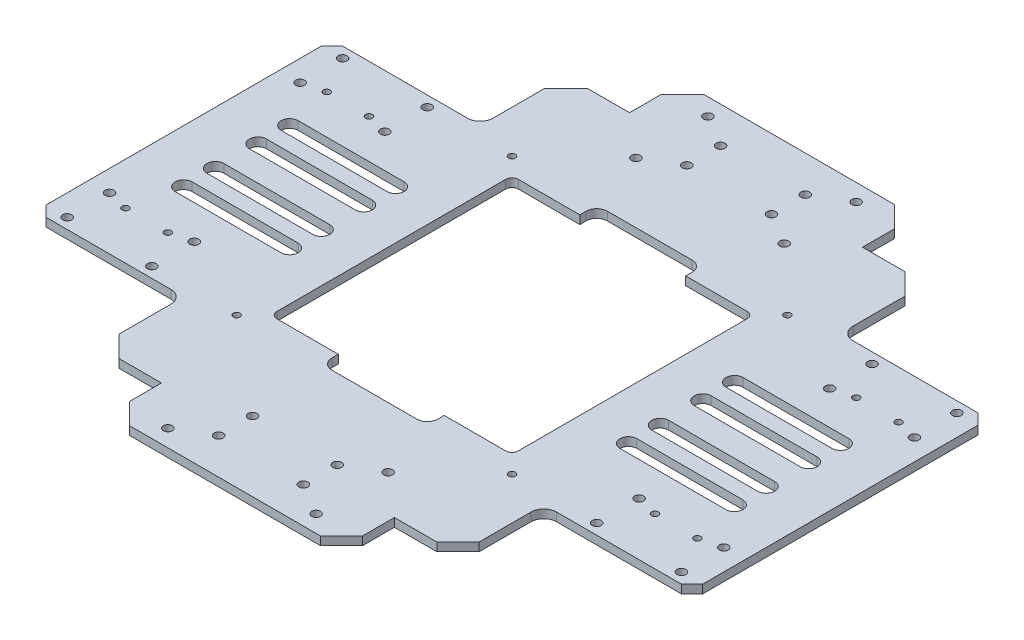
SolidWorks part; units mm, degrees
ref_plane "前视基准面" through (0, 0, 0) normal (0, 0, 1) x (1, 0, 0)
ref_plane "上视基准面" through (0, 0, 0) normal (0, 1, 0) x (1, 0, 0)
ref_plane "右视基准面" through (0, 0, 0) normal (1, 0, 0) x (0, 0, -1)
sketch "草图1" plane through (0, 0, 0) normal (0, 1, 0) x (1, 0, 0)
  line L0 (-55, 135.4999) -> (-55, -135.4999)
  line L1 (-55, -135.4999) -> (55, -135.4999)
  line L2 (55, -135.4999) -> (55, 135.4999)
  line L3 (55, 135.4999) -> (-55, 135.4999)
  circle A0 centre (-35, 127.4999) radius 2.1
  circle A1 centre (-20, 118.4999) radius 2.1
  circle A2 centre (20, 118.4999) radius 2.1
  circle A3 centre (35, 127.4999) radius 2.1
  circle A4 centre (20, 102.4999) radius 2.1
  circle A5 centre (35, 93.4999) radius 2.1
  circle A6 centre (-35, 93.4999) radius 2.1
  circle A7 centre (-20, 102.4999) radius 2.1
  circle A8 centre (-35, -127.4999) radius 2.1
  circle A9 centre (-20, -118.4999) radius 2.1
  circle A10 centre (-20, -102.4999) radius 2.1
  circle A11 centre (20, -118.4999) radius 2.1
  circle A12 centre (20, -102.4999) radius 2.1
  circle A13 centre (35, -93.4999) radius 2.1
  circle A14 centre (35, -127.4999) radius 2.1
extrude "凸台-拉伸1" add sketch "草图1" along normal blind 4
chamfer "倒角1" distance 10 angle 45 4 edges at (-55, 2, 135.4999) (55, 2, 135.4999) (55, 2, -135.4999) (-55, 2, -135.4999)
sketch "草图2" plane through (0, 4, 0) normal (0, 1, 0) x (1, 0, 0)
  line L0 (-25, 45) -> (-40, 30)
  line L1 (-25, -65) -> (25, -65)
  line L2 (-25, -65) -> (-25, -45)
  line L3 (-25, 65) -> (25, 65)
  line L4 (25, -65) -> (25, -45)
  line L5 (-25, -65) -> (25, 65) construction
  line L6 (-25, 65) -> (25, -65) construction
  line L7 (-40, 30) -> (-40, -30)
  line L8 (25, 45) -> (25, 65)
  line L9 (-25, 45) -> (-25, 65)
  line L10 (0, 65) -> (0, -65) construction
  line L11 (25, 0) -> (-25, 0) construction
  line L13 (25, 45) -> (40, 30)
  line L14 (40, 30) -> (40, -30)
  line L15 (25, -45) -> (40, -30)
  line L16 (-25, -45) -> (-40, -30)
  point P0 (0, 0)
  dimension "D1" = 130
  dimension "D2" = 50
  dimension "D5" = 20
extrude "切除-拉伸1" cut sketch "草图2" against normal blind 4
fillet "圆角1" radius 5 4 edges at (-25, 2, 65) (25, 2, 65) (25, 2, -65) (-25, 2, -65)
sketch "草图3" plane through (0, 4, 0) normal (0, 1, 0) x (1, 0, 0)
  line L0 (55, 110.4999) -> (85, 110.4999)
  line L1 (-55, 125.4999) -> (-55, -125.4999) construction
  line L2 (-85, 93.4999) -> (-85, -102.4999)
  line L3 (55, -102.4999) -> (55, 93.4999)
  line L4 (-55, -102.4999) -> (-55, 93.4999)
  line L5 (0, 135.4999) -> (0, -135.4999) construction
  line L6 (45, 135.4999) -> (-45, 135.4999) construction
  line L7 (-45, -135.4999) -> (45, -135.4999) construction
  line L10 (85, 93.4999) -> (85, -102.4999)
  line L12 (55, -125.4999) -> (55, 125.4999) construction
  line L13 (-55, 110.4999) -> (-85, 110.4999)
  line L14 (-85, 110.4999) -> (-85, 93.4999)
  line L15 (-55, 93.4999) -> (-55, 110.4999)
  line L16 (85, 110.4999) -> (85, 93.4999)
  line L17 (55, 110.4999) -> (55, 93.4999)
  line L20 (-55, -110.4999) -> (-85, -110.4999)
  line L21 (-85, -110.4999) -> (-85, -102.4999)
  line L22 (-55, -102.4999) -> (-55, -110.4999)
  line L23 (85, -102.4999) -> (85, -110.4999)
  line L24 (85, -110.4999) -> (55, -110.4999)
  line L25 (55, -110.4999) -> (55, -102.4999)
extrude "凸台-拉伸2" add sketch "草图3" against normal blind 4
chamfer "倒角2" distance 10 angle 45 4 edges at (-85, 2, 110.4999) (85, 2, 110.4999) (85, 2, -110.4999) (-85, 2, -110.4999)
fillet "圆角3" radius 5 4 edges at (-40, 2, 30) (40, 2, 30) (40, 2, -30) (-40, 2, -30)
sketch "草图5" plane through (0, 4, 0) normal (0, 1, 0) x (1, 0, 0)
  line L1 (-65, -65) -> (65, -65) construction
  line L2 (-65, -65) -> (-65, 65) construction
  line L3 (-65, 65) -> (65, 65) construction
  line L4 (65, -65) -> (65, 65) construction
  line L5 (-65, -65) -> (65, 65) construction
  line L6 (-65, 65) -> (65, -65) construction
  circle A0 centre (-65, 65) radius 1.6
  circle A1 centre (65, 65) radius 1.6
  circle A2 centre (65, -65) radius 1.6
  circle A3 centre (-65, -65) radius 1.6
  point P0 (0, 0)
  dimension "D1" = 130
  dimension "D2" = 130
extrude "切除-拉伸2" cut sketch "草图5" against normal blind 4
sketch "草图7" plane through (0, 4, 0) normal (0, 1, 0) x (1, 0, 0)
  line L0 (-85, 0) -> (-85, 70)
  line L1 (-85, 100.4999) -> (-85, -100.4999) construction
  line L2 (-85, 70) -> (-155, 70)
  line L3 (-155, 70) -> (-155, -70)
  line L4 (-155, -70) -> (-85, -70)
  line L5 (-85, -70) -> (-85, 0)
  line L6 (85, 70) -> (155, 70)
  line L7 (85, -100.4999) -> (85, 100.4999) construction
  line L8 (155, 70) -> (155, -70)
  line L9 (155, -70) -> (85, -70)
  line L10 (85, -70) -> (85, 70)
extrude "凸台-拉伸3" add sketch "草图7" against normal blind 4
fillet "圆角4" radius 6 12 edges
sketch "草图8" plane through (0, 4, 0) normal (0, 1, 0) x (1, 0, 0)
  line L0 (0, 135.4999) -> (0, 0) construction
  circle A0 centre (105, 65) radius 2.1
  circle A1 centre (145, 65) radius 2.1
  circle A2 centre (145, 45) radius 2.1
  circle A3 centre (105, 45) radius 2.1
  circle A4 centre (145, -45) radius 2.1
  circle A5 centre (145, -65) radius 2.1
  circle A6 centre (105, -65) radius 2.1
  circle A7 centre (105, -45) radius 2.1
  circle A8 centre (-145, 65) radius 2.1
  circle A9 centre (-105, 65) radius 2.1
  circle A10 centre (-105, 45) radius 2.1
  circle A11 centre (-145, 45) radius 2.1
  circle A12 centre (-145, -45) radius 2.1
  circle A13 centre (-105, -45) radius 2.1
  circle A14 centre (-105, -65) radius 2.1
  circle A15 centre (-145, -65) radius 2.1
extrude "切除-拉伸3" cut sketch "草图8" against normal blind 4
sketch "草图9" plane through (0, 4, 0) normal (0, 1, 0) x (1, 0, 0)
  line L0 (-105, 42.9) -> (-105, 25.0287) construction
  line L1 (-130, 25.0287) -> (-80, 25.0287) construction
  line L2 (-130, 29.0287) -> (-80, 29.0287)
  line L3 (-130, 21.0287) -> (-80, 21.0287)
  line L4 (-130, 10.0287) -> (-80, 10.0287) construction
  line L5 (-130, 14.0287) -> (-80, 14.0287)
  line L6 (-130, 6.0287) -> (-80, 6.0287)
  line L7 (-155, 0) -> (0, 0) construction
  line L8 (-155, 70) -> (-155, -70) construction
  line L9 (0, 0) -> (0, 135.4999) construction
  line L10 (45, 135.4999) -> (-45, 135.4999) construction
  line L11 (-130, -25.0287) -> (-80, -25.0287) construction
  line L12 (-130, -29.0287) -> (-80, -29.0287)
  line L13 (-130, -21.0287) -> (-80, -21.0287)
  line L14 (-130, -10.0287) -> (-80, -10.0287) construction
  line L15 (-130, -14.0287) -> (-80, -14.0287)
  line L16 (-130, -6.0287) -> (-80, -6.0287)
  line L17 (130, 25.0287) -> (80, 25.0287) construction
  line L18 (130, 29.0287) -> (80, 29.0287)
  line L19 (130, 21.0287) -> (80, 21.0287)
  line L20 (130, 10.0287) -> (80, 10.0287) construction
  line L21 (130, 14.0287) -> (80, 14.0287)
  line L22 (130, 6.0287) -> (80, 6.0287)
  line L23 (130, -25.0287) -> (80, -25.0287) construction
  line L24 (130, -29.0287) -> (80, -29.0287)
  line L25 (130, -21.0287) -> (80, -21.0287)
  line L26 (130, -10.0287) -> (80, -10.0287) construction
  line L27 (130, -14.0287) -> (80, -14.0287)
  line L28 (130, -6.0287) -> (80, -6.0287)
  line L29 (-145, 45) -> (-145, 47.5) construction
  line L30 (-145, 47.5) -> (-105, 47.5) construction
  line L31 (-105, 47.5) -> (-105, 45) construction
  line L32 (-125, 47.5) -> (-125, 56.2221) construction
  line L33 (-125, -47.5) -> (-125, -56.2221) construction
  line L34 (-105, -47.5) -> (-105, -45) construction
  line L35 (-145, -47.5) -> (-105, -47.5) construction
  line L36 (-145, -45) -> (-145, -47.5) construction
  line L37 (145, -45) -> (145, -47.5) construction
  line L38 (145, -47.5) -> (105, -47.5) construction
  line L39 (105, -47.5) -> (105, -45) construction
  line L40 (125, -47.5) -> (125, -56.2221) construction
  line L41 (125, 47.5) -> (125, 56.2221) construction
  line L42 (105, 47.5) -> (105, 45) construction
  line L43 (145, 47.5) -> (105, 47.5) construction
  line L44 (145, 45) -> (145, 47.5) construction
  circle A0 centre (-105, 45) radius 2.1 construction
  arc A1 (-130, 29.0287) -> (-130, 21.0287) centre (-130, 25.0287) ccw
  arc A2 (-80, 21.0287) -> (-80, 29.0287) centre (-80, 25.0287) ccw
  arc A3 (-130, 14.0287) -> (-130, 6.0287) centre (-130, 10.0287) ccw
  arc A4 (-80, 6.0287) -> (-80, 14.0287) centre (-80, 10.0287) ccw
  arc A5 (-130, -29.0287) -> (-130, -21.0287) centre (-130, -25.0287) cw
  arc A6 (-80, -21.0287) -> (-80, -29.0287) centre (-80, -25.0287) cw
  arc A7 (-130, -14.0287) -> (-130, -6.0287) centre (-130, -10.0287) cw
  arc A8 (-80, -6.0287) -> (-80, -14.0287) centre (-80, -10.0287) cw
  arc A9 (130, 29.0287) -> (130, 21.0287) centre (130, 25.0287) cw
  arc A10 (80, 21.0287) -> (80, 29.0287) centre (80, 25.0287) cw
  arc A11 (130, 14.0287) -> (130, 6.0287) centre (130, 10.0287) cw
  arc A12 (80, 6.0287) -> (80, 14.0287) centre (80, 10.0287) cw
  arc A13 (130, -29.0287) -> (130, -21.0287) centre (130, -25.0287) ccw
  arc A14 (80, -21.0287) -> (80, -29.0287) centre (80, -25.0287) ccw
  arc A15 (130, -14.0287) -> (130, -6.0287) centre (130, -10.0287) ccw
  arc A16 (80, -6.0287) -> (80, -14.0287) centre (80, -10.0287) ccw
  circle A17 centre (-135, 47.5) radius 1.6
  circle A18 centre (-115, 47.5) radius 1.6
  circle A19 centre (-115, -47.5) radius 1.6
  circle A20 centre (-135, -47.5) radius 1.6
  circle A21 centre (135, -47.5) radius 1.6
  circle A22 centre (115, -47.5) radius 1.6
  circle A23 centre (115, 47.5) radius 1.6
  circle A24 centre (135, 47.5) radius 1.6
  point P7 (-105, 25.0287)
  point P15 (-105, 10.0287)
  point P29 (-105, -25.0287)
  point P36 (-105, -10.0287)
  point P43 (105, 25.0287)
  point P50 (105, 10.0287)
  point P57 (105, -25.0287)
  point P64 (105, -10.0287)
  dimension "D1" = 4
  dimension "D4" = 10
  dimension "D2" = 50
  dimension "D3" = 2
extrude "切除-拉伸4" cut sketch "草图9" against normal blind 4
chamfer "倒角3" distance 5 angle 45 4 edges at (155, 2, -70) (155, 2, 70) (-155, 2, 70) (-155, 2, -70)
sketch "草图11" plane through (0, 4, 0) normal (0, 1, 0) x (1, 0, 0)
  line L0 (-55, 55.0142) -> (55, 55.0142) construction
  line L1 (-55, 55.0142) -> (-55, -55.0142) construction
  line L2 (-55, -55.0142) -> (55, -55.0142) construction
  line L3 (55, 55.0142) -> (55, -55.0142) construction
  line L4 (-55, 55.0142) -> (55, -55.0142) construction
  line L5 (-55, -55.0142) -> (55, 55.0142) construction
  line L6 (-57, 57.0142) -> (57, 57.0142)
  line L7 (57, 57.0142) -> (57, -57.0142)
  line L8 (-57, -57.0142) -> (57, -57.0142)
  line L9 (-57, 57.0142) -> (-57, -57.0142)
  point P0 (0, 0)
  dimension "D1" = 2
extrude "切除-拉伸5" cut sketch "草图11" against normal blind 10
fillet "圆角5" radius 3 4 edges at (-57, 2, 57.0142) (57, 2, 57.0142) (57, 2, -57.0142) (-57, 2, -57.0142)
